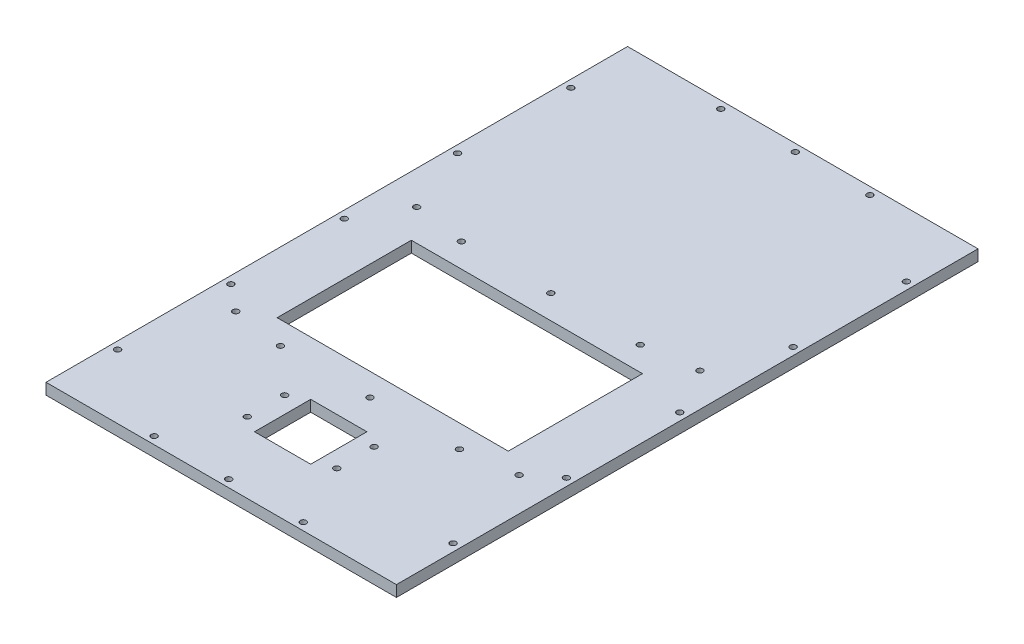
SolidWorks part; units mm, degrees
material "Acrylic (Medium-high impact)"
ref_plane "Front Plane" through (0, 0, 0) normal (0, 0, 1) x (1, 0, 0)
ref_plane "Top Plane" through (0, 0, 0) normal (0, 1, 0) x (1, 0, 0)
ref_plane "Right Plane" through (0, 0, 0) normal (1, 0, 0) x (0, 0, -1)
sketch "Sketch1" plane through (0, 0, 0) normal (0, 1, 0) x (1, 0, 0)
  line L1 (-149.225, -247.65) -> (149.225, -247.65)
  line L2 (-149.225, -247.65) -> (-149.225, 247.65)
  line L3 (-149.225, 247.65) -> (149.225, 247.65)
  line L4 (149.225, -247.65) -> (149.225, 247.65)
  line L5 (-149.225, -247.65) -> (149.225, 247.65) construction
  line L6 (-149.225, 247.65) -> (149.225, -247.65) construction
  line L7 (73.025, -247.65) -> (-130.175, -247.65)
  line L11 (-384.175, -247.65) -> (-231.775, -247.65)
  point P0 (0, 0)
  dimension "D1" = 298.45
  dimension "D2" = 495.3
extrude "Boss-Extrude1" add sketch "Sketch1" along normal mid plane 9.525 contours L1 L4 L3 L2
sketch "Sketch2" [suppressed] plane through (0, 0, 0) normal (0, 1, 0) x (1, 0, 0)
  line L0 (-250.825, -28.575) -> (250.825, -28.575) construction
  line L1 (161.925, -28.575) -> (60.325, -28.575)
  line L2 (161.925, -28.575) -> (161.925, -92.075)
  line L3 (161.925, -92.075) -> (60.325, -92.075)
  line L4 (60.325, -28.575) -> (60.325, -92.075)
  line L5 (0, -5.2388) -> (0, 5.2388) construction
  line L6 (-79.375, -28.575) -> (-168.275, -28.575)
  line L7 (-79.375, -28.575) -> (-79.375, -92.075)
  line L8 (-79.375, -92.075) -> (-168.275, -92.075)
  line L9 (-168.275, -28.575) -> (-168.275, -92.075)
  line L10 (250.825, -28.575) -> (250.825, 28.575) construction
  line L11 (-250.825, -28.575) -> (-250.825, 28.575) construction
  line L12 (-250.825, 28.575) -> (250.825, 28.575) construction
  line L13 (250.825, -28.575) -> (250.825, 28.575) construction
  line L14 (161.925, -28.575) -> (250.825, -28.575)
  line L15 (161.925, -28.575) -> (161.925, -71.755)
  line L16 (161.925, -71.755) -> (250.825, -71.755)
  line L17 (250.825, -28.575) -> (250.825, -71.755)
  line L18 (-250.825, -28.575) -> (-250.825, 28.575) construction
  line L19 (-79.375, -28.575) -> (60.325, -28.575)
  line L20 (-79.375, -28.575) -> (-79.375, -53.975)
  line L21 (-79.375, -53.975) -> (60.325, -53.975)
  line L22 (60.325, -28.575) -> (60.325, -53.975)
  line L23 (-168.275, -28.575) -> (-250.825, -28.575)
  line L24 (-168.275, -28.575) -> (-168.275, -71.755)
  line L25 (-168.275, -71.755) -> (-250.825, -71.755)
  line L26 (-250.825, -28.575) -> (-250.825, -71.755)
  point P19 (60.325, -92.075)
  dimension "D1" = 139.7
  dimension "D2" = 88.9
  dimension "D3" = 82.55
  dimension "D4" = 79.375
  dimension "D5" = 120.65
  dimension "D6" = 43.18
  dimension "D7" = 25.4
  dimension "D8" = 43.18
extrude "Boss-Extrude2" [suppressed] add sketch "Sketch2" along normal mid plane 9.525 contours L6 L9 L8 L7 | L23 L26 L25 L9 | L7 L21 L4 L19 | L17 L14 L2 L16
sketch "Sketch3" plane through (0, 4.7625, 0) normal (0, 1, 0) x (1, 0, 0)
  line L0 (-149.225, 247.65) -> (149.225, 247.65) construction
  line L1 (-98.425, 12.7) -> (98.425, 12.7)
  line L2 (-98.425, 12.7) -> (-98.425, -101.6)
  line L3 (-98.425, -101.6) -> (98.425, -101.6)
  line L4 (98.425, 12.7) -> (98.425, -101.6)
  line L5 (-98.425, 12.7) -> (98.425, -101.6) construction
  line L6 (-98.425, -101.6) -> (98.425, 12.7) construction
  line L7 (-149.225, -247.65) -> (149.225, -247.65) construction
  point P0 (0, -44.45)
  point P7 (0, 247.65)
  point P8 (0, 12.7)
  dimension "D1" = 196.85
  dimension "D2" = 114.3
  dimension "D3" = 203.2
extrude "Cut-Extrude1" cut sketch "Sketch3" against normal through all and the other way through all
sketch "Sketch4" [suppressed] plane through (0, -4.7625, 0) normal (0, -1, 0) x (1, 0, 0)
  line L0 (-107.315, 31.75) -> (107.315, 31.75) construction
  line L1 (-107.315, 33.9979) -> (107.315, 33.9979)
  line L2 (-107.315, 29.5021) -> (107.315, 29.5021)
  line L3 (-107.315, 6.35) -> (107.315, 6.35) construction
  line L4 (-107.315, 8.5979) -> (107.315, 8.5979)
  line L5 (-107.315, 4.1021) -> (107.315, 4.1021)
  arc A0 (-107.315, 33.9979) -> (-107.315, 29.5021) centre (-107.315, 31.75) ccw
  arc A1 (107.315, 29.5021) -> (107.315, 33.9979) centre (107.315, 31.75) ccw
  arc A2 (-107.315, 8.5979) -> (-107.315, 4.1021) centre (-107.315, 6.35) ccw
  arc A3 (107.315, 4.1021) -> (107.315, 8.5979) centre (107.315, 6.35) ccw
  point P0 (-107.315, 31.75)
  point P1 (107.315, 31.75)
  point P3 (107.315, 6.35)
  point P5 (-107.315, 6.35)
  point P10 (0, 31.75)
  point P15 (0, 6.35)
  dimension "D1" = 4.4958
  dimension "D2" = 4.4958
extrude "Cut-Extrude2" [suppressed] cut sketch "Sketch4" against normal through all
sketch "Sketch5" [suppressed] plane through (0, -4.7625, 0) normal (0, -1, 0) x (1, 0, 0)
  line L0 (69.85, 79.375) -> (69.85, -9.525) construction
  line L1 (60.325, 53.975) -> (60.325, 92.075) construction
  line L2 (161.925, 92.075) -> (60.325, 92.075) construction
  line L3 (-247.65, -22.225) -> (247.65, -22.225) construction
  line L4 (69.85, 79.375) -> (69.85, -9.525) construction
  line L5 (72.0979, 79.375) -> (72.0979, -9.525)
  line L6 (67.6021, 79.375) -> (67.6021, -9.525)
  line L7 (-88.9, 79.375) -> (-88.9, -9.525) construction
  line L8 (-79.375, 53.975) -> (-79.375, 92.075) construction
  line L9 (-79.375, 92.075) -> (-168.275, 92.075) construction
  line L10 (-88.9, 79.375) -> (-88.9, -9.525) construction
  line L11 (-86.6521, 79.375) -> (-86.6521, -9.525)
  line L12 (-91.1479, 79.375) -> (-91.1479, -9.525)
  arc A0 (72.0979, 79.375) -> (67.6021, 79.375) centre (69.85, 79.375) ccw
  arc A1 (67.6021, -9.525) -> (72.0979, -9.525) centre (69.85, -9.525) ccw
  arc A2 (-86.6521, 79.375) -> (-91.1479, 79.375) centre (-88.9, 79.375) ccw
  arc A3 (-91.1479, -9.525) -> (-86.6521, -9.525) centre (-88.9, -9.525) ccw
  point P8 (69.85, 34.925)
  point P19 (-88.9, 34.925)
  dimension "D1" = 9.525
  dimension "D2" = 12.7
  dimension "D3" = 12.7
  dimension "D4" = 4.4958
  dimension "D5" = 9.525
  dimension "D6" = 12.7
  dimension "D7" = 12.7
  dimension "D8" = 4.4958
extrude "Cut-Extrude3" [suppressed] cut sketch "Sketch5" against normal through all contours L12 A3 L11 A2 | L6 A1 L5 A0
sketch "Sketch6" [suppressed] plane through (0, 3.175, 0) normal (0, 1, 0) x (1, 0, 0)
  line L0 (-79.375, -38.1) -> (-79.375, 38.1) construction
  line L1 (-88.9, -50.8) -> (-88.9, 50.8) construction
  line L2 (-88.9, -50.8) -> (88.9, -50.8) construction
  line L3 (-88.9, 50.8) -> (88.9, 50.8) construction
  line L4 (79.375, -38.1) -> (79.375, 38.1) construction
  line L5 (88.9, -50.8) -> (88.9, 50.8) construction
  line L6 (-79.375, -38.1) -> (-79.375, 38.1) construction
  line L7 (-81.6229, -38.1) -> (-81.6229, 38.1)
  line L8 (-77.1271, -38.1) -> (-77.1271, 38.1)
  line L9 (79.375, -38.1) -> (79.375, 38.1) construction
  line L10 (77.1271, -38.1) -> (77.1271, 38.1)
  line L11 (81.6229, -38.1) -> (81.6229, 38.1)
  arc A0 (-81.6229, -38.1) -> (-77.1271, -38.1) centre (-79.375, -38.1) ccw
  arc A1 (-77.1271, 38.1) -> (-81.6229, 38.1) centre (-79.375, 38.1) ccw
  arc A2 (77.1271, -38.1) -> (81.6229, -38.1) centre (79.375, -38.1) ccw
  arc A3 (81.6229, 38.1) -> (77.1271, 38.1) centre (79.375, 38.1) ccw
  point P12 (-79.375, 0)
  point P17 (79.375, 0)
  dimension "D1" = 9.525
  dimension "D2" = 12.7
  dimension "D3" = 12.7
  dimension "D4" = 9.525
  dimension "D5" = 12.7
  dimension "D6" = 12.7
  dimension "D7" = 4.4958
  dimension "D8" = 4.4958
extrude "Cut-Extrude4" [suppressed] cut sketch "Sketch6" against normal through all
sketch "Sketch7" [suppressed] plane through (0, 4.7625, 0) normal (0, 1, 0) x (1, 0, 0)
  point P0 (115.1313, 66.802)
  point P1 (139.827, 42.1063)
  point P3 (-139.827, 42.1063)
  point P5 (-115.1313, 66.802)
hole_wizard "#12 Clearance Hole1" [suppressed] positions "Sketch8" profile "Sketch9" hole size "#12" standard "ANSI Inch"
sketch "Sketch8" plane through (0, 4.7625, 0) normal (0, 1, 0) x (1, 0, 0)
  point P0 (-139.827, 42.1063)
  point P3 (-115.1313, 66.802)
  point P6 (115.1313, 66.802)
  point P9 (139.827, 42.1063)
sketch "Sketch9" plane through (-139.827, 4.7625, -42.1063) normal (1, 0, 0) x (0, 0, 1)
  line L0 (0, 0) -> (0, 18.1964)
  line L1 (0, 18.1964) -> (2.8067, 16.51)
  line L2 (2.8067, 16.51) -> (2.8067, 0)
  line L5 (2.8067, 0) -> (0, 0)
  line L10 (0, 18.1964) -> (-2.8067, 16.51) construction
  line L11 (0, -6.35) -> (0, 107.95) construction
  dimension "Hole Dia." = 5.6134
  dimension "Hole Depth" = 16.51
  dimension "Drill Angle" = 118
sketch "Sketch10" [suppressed] plane through (0, -4.7625, 0) normal (0, -1, 0) x (1, 0, 0)
  point P0 (223.8375, -6.35)
  point P1 (223.8375, 19.05)
  point P3 (-223.8375, 19.05)
  point P5 (-223.8375, -6.35)
hole_wizard "#12 Clearance Hole3" [suppressed] positions "Sketch11" profile "Sketch12" hole size "#12" standard "ANSI Inch"
sketch "Sketch11" plane through (0, -4.7625, 0) normal (0, -1, 0) x (-1, 0, 0)
  point P0 (-223.8375, -19.05)
  point P3 (-223.8375, 6.35)
  point P6 (223.8375, -19.05)
  point P9 (223.8375, 6.35)
sketch "Sketch12" plane through (223.8375, -4.7625, 19.05) normal (1, 0, 0) x (0, 0, -1)
  line L0 (0, 0) -> (0, 18.1964)
  line L1 (0, 18.1964) -> (2.8067, 16.51)
  line L2 (2.8067, 16.51) -> (2.8067, 0)
  line L5 (2.8067, 0) -> (0, 0)
  line L10 (0, 18.1964) -> (-2.8067, 16.51) construction
  line L11 (0, -6.35) -> (0, 107.95) construction
  dimension "Hole Dia." = 5.6134
  dimension "Hole Depth" = 16.51
  dimension "Drill Angle" = 118
sketch "Sketch13" [suppressed] plane through (0, -4.7625, 0) normal (0, -1, 0) x (1, 0, 0)
  point P0 (133.35, -223.8375)
  point P1 (107.95, -223.8375)
  point P3 (-107.95, -223.8375)
  point P5 (-133.35, -223.8375)
  point P7 (133.35, 223.8375)
  point P9 (107.95, 223.8375)
  point P11 (-107.95, 223.8375)
  point P13 (-133.35, 223.8375)
hole_wizard "#12 Clearance Hole2" [suppressed] positions "Sketch14" profile "Sketch15" hole size "#12" standard "ANSI Inch"
sketch "Sketch14" [suppressed] plane through (0, -4.7625, 0) normal (0, -1, 0) x (-1, 0, 0)
  point P0 (107.95, -223.8375)
  point P3 (133.35, -223.8375)
  point P6 (133.35, 223.8375)
  point P9 (107.95, 223.8375)
  point P12 (-133.35, 223.8375)
  point P15 (-107.95, 223.8375)
  point P18 (-133.35, -223.8375)
  point P21 (-107.95, -223.8375)
sketch "Sketch15" plane through (-107.95, -4.7625, 223.8375) normal (1, 0, 0) x (0, 0, -1)
  line L0 (0, 0) -> (0, 18.1964)
  line L1 (0, 18.1964) -> (2.8067, 16.51)
  line L2 (2.8067, 16.51) -> (2.8067, 0)
  line L5 (2.8067, 0) -> (0, 0)
  line L10 (0, 18.1964) -> (-2.8067, 16.51) construction
  line L11 (0, -6.35) -> (0, 107.95) construction
  dimension "Hole Dia." = 5.6134
  dimension "Hole Depth" = 16.51
  dimension "Drill Angle" = 118
sketch "Sketch16" [suppressed] plane through (0, 3.175, 0) normal (0, 1, 0) x (1, 0, 0)
  line L0 (88.9, -50.8) -> (88.9, 50.8) construction
  line L1 (-88.9, -50.8) -> (-88.9, 50.8) construction
  line L2 (-88.9, -50.8) -> (88.9, -50.8) construction
  point P0 (79.375, -38.1)
  point P1 (-79.375, -38.1)
  dimension "D1" = 9.525
  dimension "D2" = 9.525
  dimension "D3" = 12.7
hole_wizard "#8 Clearance Hole1" [suppressed] positions "Sketch17" profile "Sketch19" hole size "#8" standard "ANSI Inch"
sketch "Sketch17" plane through (0, 3.175, 0) normal (0, 1, 0) x (1, 0, 0)
  point P0 (79.375, -38.1)
  point P3 (-79.375, -38.1)
sketch "Sketch19" plane through (79.375, 3.175, 38.1) normal (1, 0, 0) x (0, 0, 1)
  line L0 (0, 0) -> (0, 12.0187)
  line L1 (0, 12.0187) -> (2.2479, 10.668)
  line L2 (2.2479, 10.668) -> (2.2479, 0)
  line L5 (2.2479, 0) -> (0, 0)
  line L10 (0, 12.0187) -> (-2.2479, 10.668) construction
  line L11 (0, -6.35) -> (0, 107.95) construction
  dimension "Hole Dia." = 4.4958
  dimension "Hole Depth" = 10.668
  dimension "Drill Angle" = 118
sketch "Sketch20" plane through (0, -4.7625, 0) normal (0, -1, 0) x (1, 0, 0)
  line L0 (-149.225, 247.65) -> (149.225, 247.65) construction
  line L1 (23.9395, 147.5105) -> (-23.9395, 147.5105)
  line L2 (23.9395, 147.5105) -> (23.9395, 195.3895)
  line L3 (23.9395, 195.3895) -> (-23.9395, 195.3895)
  line L4 (-23.9395, 147.5105) -> (-23.9395, 195.3895)
  line L5 (23.9395, 147.5105) -> (-23.9395, 195.3895) construction
  line L6 (23.9395, 195.3895) -> (-23.9395, 147.5105) construction
  line L8 (38.1, 155.575) -> (-38.1, 155.575) construction
  line L9 (38.1, 155.575) -> (38.1, 187.325) construction
  line L10 (38.1, 187.325) -> (-38.1, 187.325) construction
  line L11 (-38.1, 155.575) -> (-38.1, 187.325) construction
  point P0 (0, 171.45)
  point P7 (0, 247.65)
  point P8 (38.1, 155.575)
  point P9 (38.1, 187.325)
  point P10 (-38.1, 155.575)
  point P11 (-38.1, 187.325)
  point P18 (0, 187.325)
  point P19 (0, 195.3895)
  point P20 (-38.1, 171.45)
  point P21 (-23.9395, 171.45)
  dimension "D1" = 47.879
  dimension "D2" = 47.879
  dimension "D3" = 38.1
  dimension "D4" = 15.875
  dimension "D5" = 76.2
extrude "Cut-Extrude5" cut sketch "Sketch20" against normal through all contours L1 L4 L3 L2
hole_wizard "#10 Clearance Hole1" positions "Sketch21" profile "Sketch22" hole size "#10" standard "ANSI Inch"
sketch "Sketch21" plane through (0, -4.7625, 0) normal (0, -1, 0) x (-1, 0, 0)
  point P0 (-38.1, -155.575)
  point P3 (38.1, -155.575)
  point P6 (38.1, -187.325)
  point P9 (-38.1, -187.325)
sketch "Sketch22" plane through (38.1, -4.7625, 155.575) normal (1, 0, 0) x (0, 0, -1)
  line L0 (0, 0) -> (0, 12.2018)
  line L1 (0, 12.2018) -> (2.5527, 10.668)
  line L2 (2.5527, 10.668) -> (2.5527, 0)
  line L5 (2.5527, 0) -> (0, 0)
  line L10 (0, 12.2018) -> (-2.5527, 10.668) construction
  line L11 (0, -6.35) -> (0, 107.95) construction
  dimension "Hole Dia." = 5.1054
  dimension "Hole Depth" = 10.668
  dimension "Drill Angle" = 118
sketch "Sketch23" [suppressed] plane through (-250.825, 0, 0) normal (-1, 0, 0) x (0, 0, 1)
  line L4 (-28.575, -4.7625) -> (71.755, -4.7625)
  line L5 (71.755, -4.7625) -> (71.755, 4.7625)
  line L6 (71.755, 4.7625) -> (-28.575, 4.7625)
  line L7 (-28.575, 4.7625) -> (-28.575, -4.7625)
  line L8 (-28.575, -4.7625) -> (71.755, -4.7625)
  line L9 (71.755, -4.7625) -> (71.755, 4.7625)
  line L10 (71.755, 4.7625) -> (-28.575, 4.7625)
  line L11 (-28.575, 4.7625) -> (-28.575, -4.7625)
  dimension "D1" = 0
extrude "Boss-Extrude3" [suppressed] add sketch "Sketch23" along normal blind 6.35
mirror "Mirror1" [suppressed] about plane through (0, 0, 0) normal (1, 0, 0)
sketch "Sketch27" [suppressed] plane through (0, 4.7625, 0) normal (0, 1, 0) x (1, 0, 0)
  line L1 (257.175, -71.755) -> (257.175, 28.575) construction
  line L2 (-257.175, 28.575) -> (257.175, 28.575) construction
  point P0 (241.3, 12.7)
  dimension "D1" = 15.875
  dimension "D2" = 15.875
hole_wizard "#10 Clearance Hole2" [suppressed] positions "Sketch28" profile "Sketch30" hole size "#10" standard "ANSI Inch"
sketch "Sketch28" plane through (0, 4.7625, 0) normal (0, 1, 0) x (1, 0, 0)
  point P0 (241.3, 12.7)
sketch "Sketch30" plane through (241.3, 4.7625, -12.7) normal (1, 0, 0) x (0, 0, 1)
  line L0 (0, 0) -> (0, 9.525)
  line L1 (0, 9.525) -> (2.5527, 9.525)
  line L2 (2.5527, 9.525) -> (2.5527, 0)
  line L5 (2.5527, 0) -> (0, 0)
  line L11 (0, -6.35) -> (0, 107.95) construction
  dimension "Thru Hole Dia." = 5.1054
  dimension "Thru Hole Depth" = 9.525
pattern_linear "LPattern1" [suppressed] count 6 spacing 96.52
sketch "Sketch31" [suppressed] plane through (0, 4.7625, 0) normal (0, 1, 0) x (1, 0, 0)
  line L1 (0, -5.2388) -> (0, 5.2388) construction
  line L2 (-149.225, 76.2) -> (149.225, 76.2) construction
  point P0 (-95.25, 60.325)
  dimension "D1" = 15.875
  dimension "D2" = 95.25
hole_wizard "#10 Clearance Hole3" [suppressed] positions "Sketch32" profile "Sketch33" hole size "#10" standard "ANSI Inch"
sketch "Sketch32" plane through (0, 4.7625, 0) normal (0, 1, 0) x (1, 0, 0)
  point P0 (-95.25, 60.325)
sketch "Sketch33" plane through (-95.25, 4.7625, -60.325) normal (1, 0, 0) x (0, 0, 1)
  line L0 (0, 0) -> (0, 9.525)
  line L1 (0, 9.525) -> (2.5527, 9.525)
  line L2 (2.5527, 9.525) -> (2.5527, 0)
  line L5 (2.5527, 0) -> (0, 0)
  line L11 (0, -6.35) -> (0, 107.95) construction
  dimension "Thru Hole Dia." = 5.1054
  dimension "Thru Hole Depth" = 9.525
pattern_linear "LPattern2" [suppressed] count 4 spacing 63.5
sketch "Sketch34" plane through (0, 4.7625, 0) normal (0, 1, 0) x (1, 0, 0)
  line L0 (0, -5.2388) -> (0, 5.2388) construction
  line L1 (-149.225, 247.65) -> (149.225, 247.65) construction
  point P0 (-63.5, 241.3)
  dimension "D1" = 63.5
  dimension "D2" = 6.35
hole_wizard "#10 Clearance Hole4" positions "Sketch35" profile "Sketch36" hole size "#10" standard "ANSI Inch" end condition up to next
sketch "Sketch35" plane through (0, 4.7625, 0) normal (0, 1, 0) x (1, 0, 0)
  point P0 (-63.5, 241.3)
sketch "Sketch36" plane through (-63.5, 4.7625, -241.3) normal (1, 0, 0) x (0, 0, 1)
  line L0 (0, 0) -> (0, 9.525)
  line L1 (0, 9.525) -> (2.5527, 9.525)
  line L2 (2.5527, 9.525) -> (2.5527, 0)
  line L5 (2.5527, 0) -> (0, 0)
  line L11 (0, -6.35) -> (0, 107.95) construction
  dimension "Thru Hole Dia." = 5.1054
  dimension "Thru Hole Depth" = 9.525
pattern_linear "LPattern3" count 3 spacing 63.5 along (1, 0, 0) of "#10 Clearance Hole4"
mirror "Mirror2" about plane through (0, 0, 0) normal (0, 0, 1) of "LPattern3", "#10 Clearance Hole4"
sketch "Sketch37" plane through (0, 4.7625, 0) normal (0, 1, 0) x (1, 0, 0)
  line L0 (-5.2388, 0) -> (5.2388, 0) construction
  line L1 (-149.225, -247.65) -> (-149.225, 247.65) construction
  point P0 (-142.875, 0)
  dimension "D1" = 6.35
hole_wizard "#10 Clearance Hole5" positions "Sketch38" profile "Sketch39" hole size "#10" standard "ANSI Inch" end condition up to next
sketch "Sketch38" plane through (0, 4.7625, 0) normal (0, 1, 0) x (1, 0, 0)
  point P0 (-142.875, 0)
sketch "Sketch39" plane through (-142.875, 4.7625, 0) normal (1, 0, 0) x (0, 0, 1)
  line L0 (0, 0) -> (0, 9.525)
  line L1 (0, 9.525) -> (2.5527, 9.525)
  line L2 (2.5527, 9.525) -> (2.5527, 0)
  line L5 (2.5527, 0) -> (0, 0)
  line L11 (0, -6.35) -> (0, 107.95) construction
  dimension "Thru Hole Dia." = 5.1054
  dimension "Thru Hole Depth" = 9.525
pattern_linear "LPattern4" count 3 spacing 96.52 along (0, 0, -1) count 3 spacing 96.52 along (0, 0, 1) of "#10 Clearance Hole5"
mirror "Mirror3" about plane through (0, 0, 0) normal (1, 0, 0) of "LPattern4", "#10 Clearance Hole5"
sketch "Sketch40" [suppressed] plane through (0, 4.7625, 0) normal (0, 1, 0) x (1, 0, 0)
  line L0 (-79.375, -53.975) -> (-79.375, -92.075) construction
  line L3 (-88.9, -79.375) -> (-88.9, -9.525) construction
  line L4 (-91.1479, -79.375) -> (-91.1479, -9.525)
  line L5 (-86.6521, -79.375) -> (-86.6521, -9.525)
  line L6 (69.85, -79.375) -> (69.85, -9.525) construction
  line L7 (67.6021, -79.375) -> (67.6021, -9.525)
  line L8 (72.0979, -79.375) -> (72.0979, -9.525)
  line L9 (60.325, -53.975) -> (60.325, -92.075) construction
  line L12 (-79.375, -92.075) -> (-168.275, -92.075) construction
  line L13 (161.925, -92.075) -> (60.325, -92.075) construction
  arc A2 (-91.1479, -79.375) -> (-86.6521, -79.375) centre (-88.9, -79.375) ccw
  arc A3 (-86.6521, -9.525) -> (-91.1479, -9.525) centre (-88.9, -9.525) ccw
  arc A4 (67.6021, -79.375) -> (72.0979, -79.375) centre (69.85, -79.375) ccw
  arc A5 (72.0979, -9.525) -> (67.6021, -9.525) centre (69.85, -9.525) ccw
  point P7 (-88.9, -44.45)
  point P14 (69.85, -44.45)
  dimension "D1" = 9.525
  dimension "D2" = 4.4958
  dimension "D3" = 4.4958
  dimension "D4" = 9.525
  dimension "D5" = 12.7
  dimension "D6" = 12.7
  dimension "D7" = 69.85
  dimension "D8" = 69.85
extrude "Cut-Extrude6" [suppressed] cut sketch "Sketch40" against normal up to next
sketch "Sketch41" plane through (0, -4.7625, 0) normal (0, -1, 0) x (1, 0, 0)
  point P0 (120.65, -39.4255)
  point P1 (-120.65, -39.4255)
  point P3 (-120.65, 114.6255)
  point P5 (120.65, 114.6255)
hole_wizard "#10 Clearance Hole6" positions "Sketch42" profile "Sketch43" hole size "#10" standard "ANSI Inch" end condition through all
sketch "Sketch42" plane through (0, 4.7625, 0) normal (0, 1, 0) x (1, 0, 0)
  point P0 (120.65, 39.4255)
  point P3 (120.65, -114.6255)
  point P6 (-120.65, -114.6255)
  point P9 (-120.65, 39.4255)
sketch "Sketch43" plane through (120.65, 4.7625, -39.4255) normal (1, 0, 0) x (0, 0, 1)
  line L0 (0, 0) -> (0, 9.525)
  line L1 (0, 9.525) -> (2.5527, 9.525)
  line L2 (2.5527, 9.525) -> (2.5527, 0)
  line L5 (2.5527, 0) -> (0, 0)
  line L11 (0, -6.35) -> (0, 107.95) construction
  dimension "Thru Hole Dia." = 5.1054
  dimension "Thru Hole Depth" = 9.525
sketch "Sketch44" plane through (0, 4.7625, 0) normal (0, 1, 0) x (1, 0, 0)
  line L0 (0, -5.2388) -> (0, 5.2388) construction
  line L1 (120.65, 39.4255) -> (-120.65, 39.4255) construction
  line L2 (120.65, -114.6255) -> (-120.65, -114.6255) construction
  point P0 (0, 33.0755)
  point P1 (0, -120.9755)
  point P4 (76.2, -120.9755)
  point P5 (76.2, 33.0755)
  point P6 (-76.2, 33.0755)
  point P7 (-76.2, -120.9755)
  point P12 (0, 0)
  dimension "D1" = 76.2
  dimension "D2" = 76.2
  dimension "D3" = 6.35
  dimension "D4" = 6.35
hole_wizard "#10 Clearance Hole7" positions "Sketch45" profile "Sketch46" hole size "#10" standard "ANSI Inch" end condition through all
sketch "Sketch45" plane through (0, 4.7625, 0) normal (0, 1, 0) x (1, 0, 0)
  point P0 (76.2, 33.0755)
  point P3 (0, 33.0755)
  point P6 (-76.2, 33.0755)
  point P9 (-76.2, -120.9755)
  point P12 (0, -120.9755)
  point P15 (76.2, -120.9755)
sketch "Sketch46" plane through (76.2, 4.7625, -33.0755) normal (1, 0, 0) x (0, 0, 1)
  line L0 (0, 0) -> (0, 9.525)
  line L1 (0, 9.525) -> (2.5527, 9.525)
  line L2 (2.5527, 9.525) -> (2.5527, 0)
  line L5 (2.5527, 0) -> (0, 0)
  line L11 (0, -6.35) -> (0, 107.95) construction
  dimension "Thru Hole Dia." = 5.1054
  dimension "Thru Hole Depth" = 9.525
